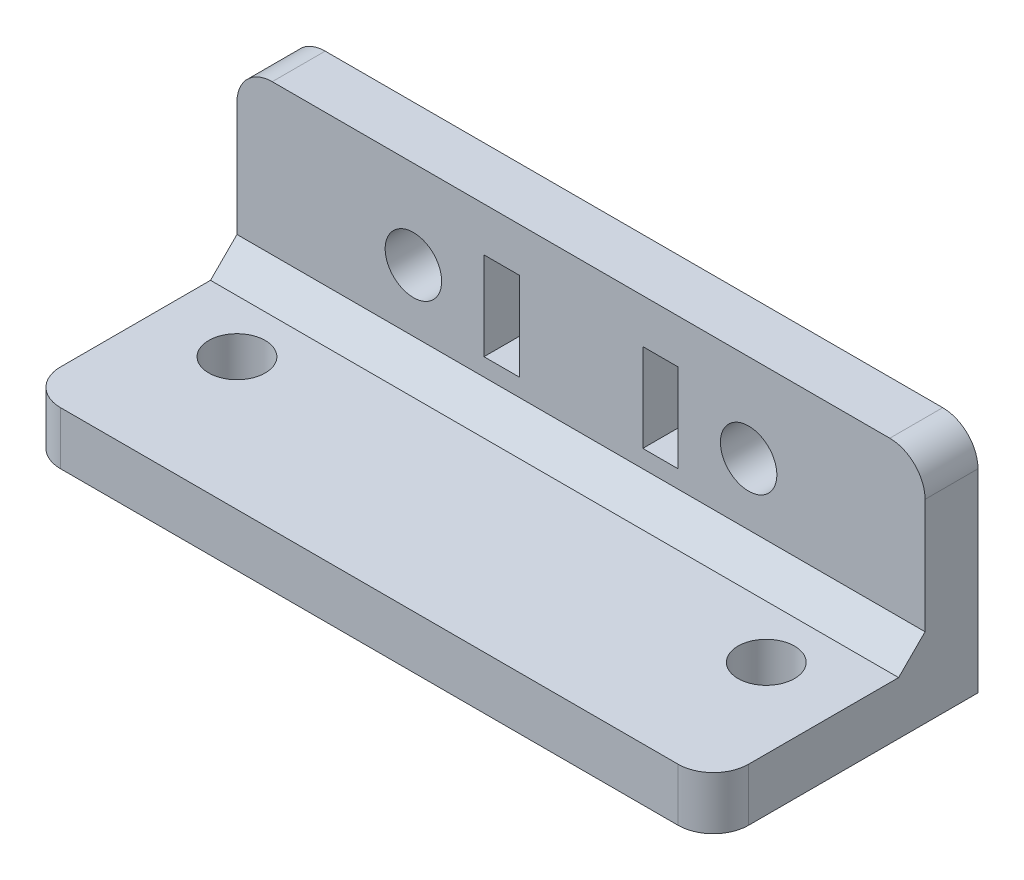
SolidWorks part; units mm, degrees
ref_plane "正面" through (0, 0, 0) normal (0, 0, 1) x (1, 0, 0)
ref_plane "平面" through (0, 0, 0) normal (0, 1, 0) x (1, 0, 0)
ref_plane "右側面" through (0, 0, 0) normal (1, 0, 0) x (0, 0, -1)
sketch "ｽｹｯﾁ1" plane through (0, 0, 0) normal (0, 0, 1) x (1, 0, 0)
  line L0 (0, 0) -> (19, 0) construction
  line L1 (0, 0) -> (-10, 0) construction
  line L2 (-10, -5) -> (-10, 5)
  line L3 (-10, 5) -> (29, 5)
  line L4 (-10, -5) -> (29, -5)
  line L5 (29, -5) -> (29, 5)
  line L6 (4, -2.5) -> (6, -2.5)
  line L7 (4, -2.5) -> (4, 2.5)
  line L8 (4, 2.5) -> (6, 2.5)
  line L9 (6, -2.5) -> (6, 2.5)
  line L10 (4, -2.5) -> (6, 2.5) construction
  line L11 (4, 2.5) -> (6, -2.5) construction
  line L12 (13, -2.5) -> (15, -2.5)
  line L13 (13, -2.5) -> (13, 2.5)
  line L14 (13, 2.5) -> (15, 2.5)
  line L15 (15, -2.5) -> (15, 2.5)
  line L16 (13, -2.5) -> (15, 2.5) construction
  line L17 (13, 2.5) -> (15, -2.5) construction
  line L18 (19, 0) -> (29, 0) construction
  circle A0 centre (0, 0) radius 1.6
  circle A1 centre (19, 0) radius 1.6
  point P8 (-10, 0)
  point P9 (5, 0)
  point P13 (14, 0)
  point P25 (29, 0)
  dimension "D1" = 3.2
  dimension "D2" = 19
  dimension "D3" = 10
  dimension "D5" = 10
  dimension "D4" = 10
  dimension "D6" = 2
  dimension "D7" = 5
  dimension "D8" = 5
  dimension "D9" = 5
extrude "ﾎﾞｽ - 押し出し1" add sketch "ｽｹｯﾁ1" along normal blind 3
sketch "ｽｹｯﾁ2" plane through (0, -5, 0) normal (0, -1, 0) x (1, 0, 0)
  line L0 (-10, 3) -> (-10, 0) construction
  line L1 (29, 0) -> (-10, 0)
  line L2 (29, 0) -> (29, 15)
  line L3 (29, 15) -> (-10, 15)
  line L4 (-10, 0) -> (-10, 15)
  line L5 (9.5, 0) -> (9.5, 15) construction
  line L6 (24.5, 7.5) -> (-5.5, 7.5) construction
  circle A0 centre (-5.5, 7.5) radius 1.6
  circle A1 centre (24.5, 7.5) radius 1.6
  point P12 (9.5, 7.5)
  dimension "D3" = 3.2
  dimension "D1" = 15
  dimension "D2" = 30
extrude "ﾎﾞｽ - 押し出し2" add sketch "ｽｹｯﾁ2" along normal blind 3
chamfer "面取り1" distance 1.5 angle 45 1 edges at (9.5, -5, 3)
fillet "ﾌｨﾚｯﾄ1" radius 2 4 edges at (-10, -6.5, 15) (29, -6.5, 15) (-10, 5, 1.5) (29, 5, 1.5)
